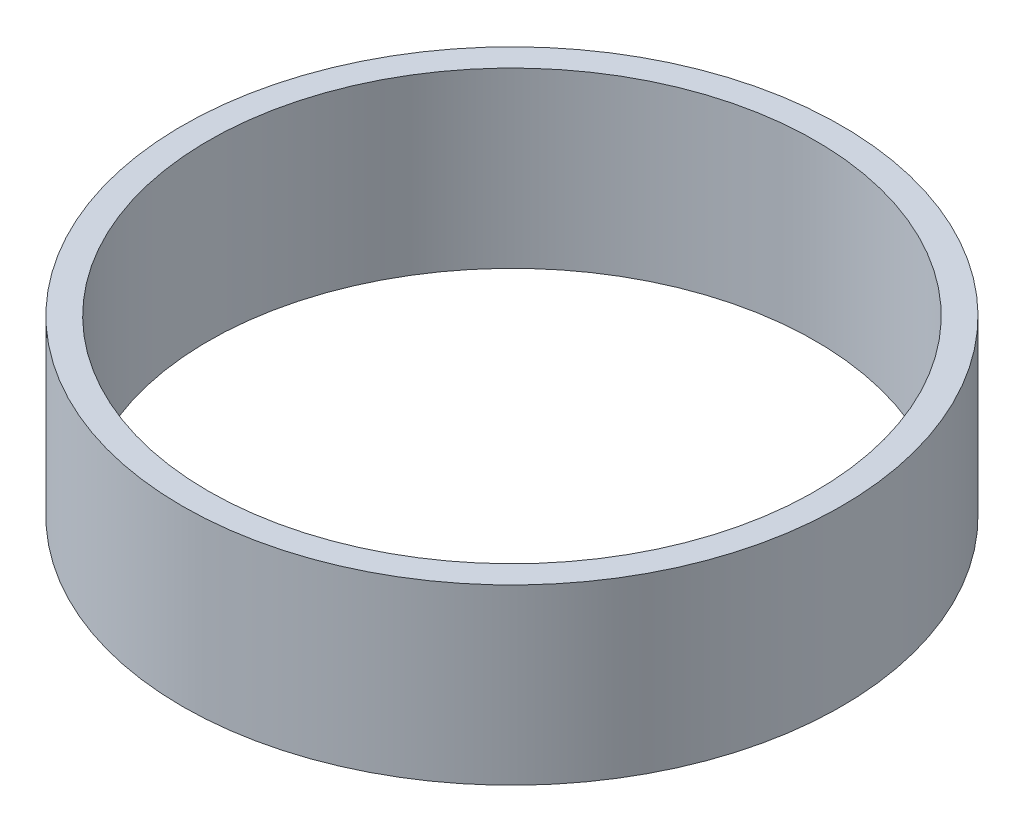
SolidWorks part; units mm, degrees
ref_plane "Front Plane" through (0, 0, 0) normal (0, 0, 1) x (1, 0, 0)
ref_plane "Top Plane" through (0, 0, 0) normal (0, 1, 0) x (1, 0, 0)
ref_plane "Right Plane" through (0, 0, 0) normal (1, 0, 0) x (0, 0, -1)
sketch "Sketch3" plane through (0, 0, 0) normal (0, 1, 0) x (1, 0, 0)
  circle A0 centre (0, 0) radius 15.2
  circle A2 centre (0, 0) radius 14
  dimension "D1" = 28
  dimension "D2" = 1.2
extrude "Boss-Extrude2" add sketch "Sketch3" along normal blind 8
